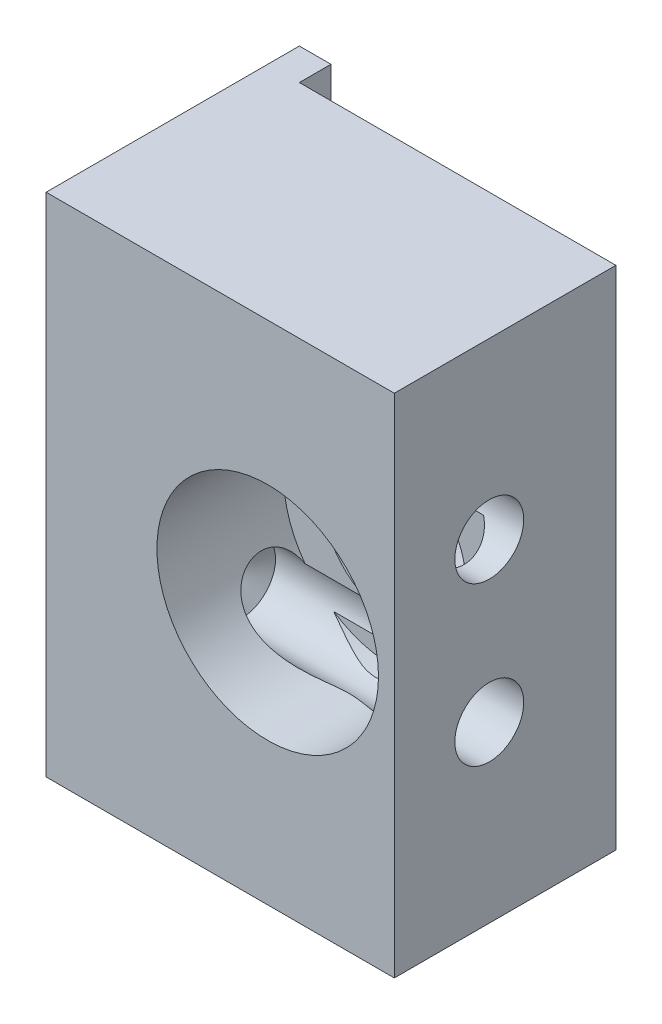
SolidWorks part; units mm, degrees
ref_plane "Front" through (0, 0, 0) normal (0, 0, 1) x (1, 0, 0)
ref_plane "Top" through (0, 0, 0) normal (0, 1, 0) x (1, 0, 0)
ref_plane "Right" through (0, 0, 0) normal (1, 0, 0) x (0, 0, -1)
sketch "Sketch1" plane through (0, 0, 0) normal (0, 0, 1) x (1, 0, 0)
  line L1 (0, 0) -> (17.4625, 0)
  line L2 (0, 0) -> (0, 25.4)
  line L3 (0, 25.4) -> (17.4625, 25.4)
  line L4 (17.4625, 0) -> (17.4625, 25.4)
  dimension "D1" = 25.4
  dimension "D2" = 17.4625
extrude "Boss-Extrude1" add sketch "Sketch1" along normal blind 12.7
sketch "Sketch2" plane through (0, 25.4, 0) normal (0, 1, 0) x (1, 0, 0)
  line L0 (17.4625, -12.7) -> (0, -12.7) construction
  line L1 (17.4625, 0) -> (1.5875, 0)
  line L2 (17.4625, 0) -> (17.4625, -1.5875)
  line L3 (17.4625, -1.5875) -> (1.5875, -1.5875)
  line L4 (1.5875, 0) -> (1.5875, -1.5875)
  line L5 (17.4625, -12.7) -> (17.4625, 0) construction
  dimension "D1" = 11.1125
  dimension "D2" = 15.875
extrude "Cut-Extrude1" cut sketch "Sketch2" against normal through all
hole_wizard "#8-32 Tapped Hole1" positions "Sketch3" profile "Sketch4" tap size "#8-32" standard "ANSI Inch"
sketch "Sketch3" plane through (17.4625, 0, 0) normal (1, 0, 0) x (0, 0, -1)
  line L0 (-1.5875, 0) -> (-1.5875, 25.4) construction
  line L1 (-12.7, 25.4) -> (-1.5875, 25.4) construction
  point P0 (-7.9375, 16.6687)
  point P2 (-7.9375, 8.7312)
  dimension "D1" = 7.9375
  dimension "D2" = 6.35
  dimension "D3" = 8.7312
cosmetic thread "Hole Thread1" parameters "D1"=8.382, "D2"=4.1656
cosmetic thread "Hole Thread2" parameters "D1"=8.382, "D2"=4.1656
sketch "Sketch4" plane through (17.4625, 16.6687, 7.9375) normal (0, 1, 0) x (0, 0, -1)
  line L0 (0, 0) -> (0, 13.4838)
  line L1 (0, 13.4838) -> (1.7272, 12.446)
  line L2 (1.7272, 12.446) -> (1.7272, 0)
  line L5 (1.7272, 0) -> (0, 0)
  line L10 (0, 13.4838) -> (-1.7272, 12.446) construction
  line L11 (0, -6.35) -> (0, 107.95) construction
  dimension "Tap Drill Dia." = 3.4544
  dimension "Tap Drill Depth" = 12.446
  dimension "Drill Angle" = 118
hole_wizard "CBORE for 1/4 Socket Head Cap Screw1" positions "Sketch5" profile "Sketch6" counterbore size "1/4" standard "ANSI Inch" end condition through all
sketch "Sketch5" plane through (0, 0, 12.7) normal (0, 0, 1) x (1, 0, 0)
  line L0 (1.5875, 0) -> (1.5875, 25.4) construction
  line L2 (0, 0) -> (17.4625, 0) construction
  point P0 (11.1125, 12.7)
  dimension "D1" = 9.525
  dimension "D2" = 12.7
sketch "Sketch6" plane through (11.1125, 12.7, 12.7) normal (1, 0, 0) x (0, -1, 0)
  line L0 (0, 0) -> (0, 12.7)
  line L1 (0, 12.7) -> (3.5712, 12.7)
  line L3 (3.5712, 12.7) -> (3.5712, 6.35)
  line L4 (3.5712, 6.35) -> (5.5562, 6.35)
  line L5 (5.5562, 6.35) -> (5.5562, 0)
  line L7 (5.5562, 0) -> (0, 0)
  line L11 (0, -6.35) -> (0, 107.95) construction
  dimension "Thru Hole Dia." = 7.1425
  dimension "Thru Hole Depth" = 12.7
  dimension "C'Bore Dia." = 11.1125
  dimension "C'Bore Depth" = 6.35
